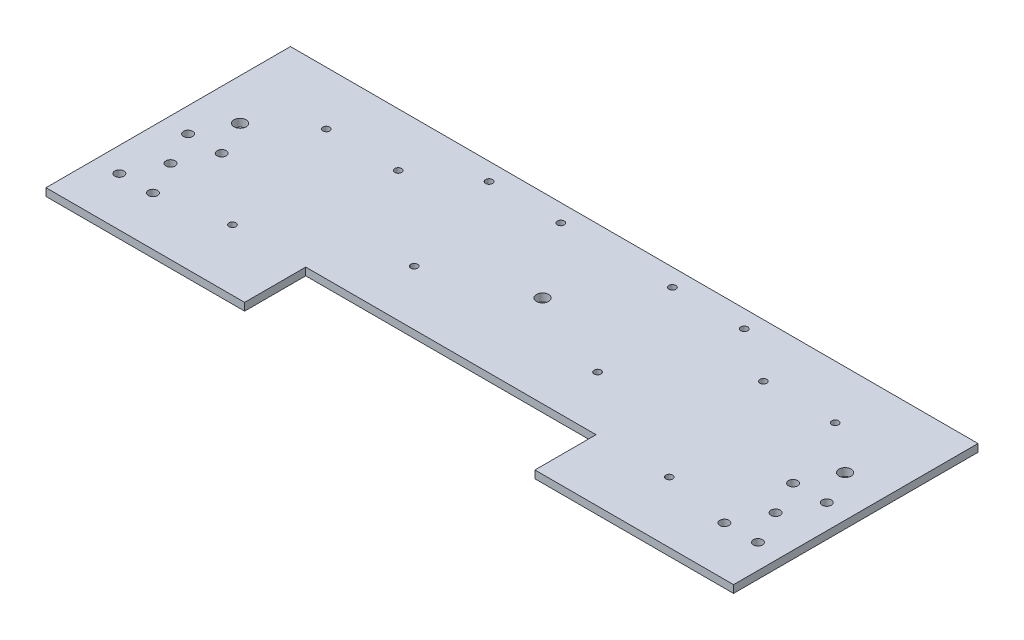
SolidWorks part; units mm, degrees
ref_plane "前视基准面" through (0, 0, 0) normal (0, 0, 1) x (1, 0, 0)
ref_plane "上视基准面" through (0, 0, 0) normal (0, 1, 0) x (1, 0, 0)
ref_plane "右视基准面" through (0, 0, 0) normal (1, 0, 0) x (0, 0, -1)
sketch "草图1" plane through (0, 0, 0) normal (0, 1, 0) x (1, 0, 0)
  line L1 (0, 0) -> (450, 0)
  line L2 (0, 0) -> (0, 120)
  line L3 (0, 120) -> (450, 120)
  line L4 (450, 0) -> (450, 120)
  dimension "D1" = 450
  dimension "D2" = 120
extrude "凸台-拉伸1" add sketch "草图1" along normal blind 5
sketch "草图2" plane through (0, 5, 0) normal (0, 1, 0) x (1, 0, 0)
  line L0 (0, 60) -> (450, 60) construction
  line L1 (0, 120) -> (0, 0) construction
  line L2 (450, 0) -> (450, 120) construction
  line L3 (225, 120) -> (225, 0) construction
  line L4 (450, 120) -> (0, 120) construction
  line L5 (0, 0) -> (450, 0) construction
  circle A0 centre (225, 60) radius 4
  circle A1 centre (27, 60) radius 4
  circle A2 centre (423, 60) radius 4
  dimension "D2" = 8
  dimension "D3" = 8
  dimension "D4" = 396
  dimension "D1" = 60
extrude "切除-拉伸1" cut sketch "草图2" against normal through all
sketch "草图3" plane through (0, 5, 0) normal (0, 1, 0) x (1, 0, 0)
  line L0 (0, 36) -> (450, 36) construction
  line L1 (0, 120) -> (0, 0) construction
  line L2 (450, 0) -> (450, 120) construction
  line L3 (0, 108.5) -> (450, 108.5) construction
  line L4 (225, 0) -> (225, 120) construction
  line L5 (0, 0) -> (450, 0) construction
  line L6 (450, 120) -> (0, 120) construction
  line L7 (165, 0) -> (165, 120) construction
  line L8 (285, 0) -> (285, 120) construction
  circle A0 centre (165, 36) radius 2.25
  circle A1 centre (141.5, 108.5) radius 2.25
  circle A2 centre (188.5, 108.5) radius 2.25
  circle A3 centre (285, 36) radius 2.25
  circle A4 centre (261.5, 108.5) radius 2.25
  circle A5 centre (308.5, 108.5) radius 2.25
  dimension "D4" = 47
  dimension "D5" = 4.5
  dimension "D6" = 4.5
  dimension "D1" = 36
  dimension "D2" = 72.5
  dimension "D3" = 60
extrude "切除-拉伸2" cut sketch "草图3" against normal through all
sketch "草图4" plane through (0, 5, 0) normal (0, 1, 0) x (1, 0, 0)
  line L0 (225, 0) -> (225, 120) construction
  line L1 (0, 0) -> (130, 0)
  line L2 (0, 0) -> (0, -40)
  line L3 (0, -40) -> (130, -40)
  line L4 (130, 0) -> (130, -40)
  line L5 (0, 0) -> (450, 0) construction
  line L6 (450, 120) -> (0, 120) construction
  line L7 (450, 0) -> (450, -40)
  line L8 (450, -40) -> (320, -40)
  line L9 (320, 0) -> (320, -40)
  line L10 (450, 0) -> (320, 0)
  dimension "D1" = 130
  dimension "D2" = 40
extrude "凸台-拉伸2" add sketch "草图4" against normal blind 5
sketch "草图5" plane through (0, 5, 0) normal (0, 1, 0) x (1, 0, 0)
  line L0 (225, 120) -> (225, 0) construction
  line L1 (450, 120) -> (0, 120) construction
  line L2 (130, 0) -> (320, 0) construction
  line L3 (82, 120) -> (82, -40) construction
  line L4 (0, -40) -> (130, -40) construction
  circle A0 centre (82, 0) radius 2.25
  circle A1 centre (58.5, 85) radius 2.25
  circle A2 centre (105.5, 85) radius 2.25
  circle A3 centre (368, 0) radius 2.25
  circle A4 centre (344.5, 85) radius 2.25
  circle A5 centre (391.5, 85) radius 2.25
  dimension "D1" = 4.5
  dimension "D2" = 4.5
  dimension "D4" = 47
  dimension "D5" = 85
  dimension "D6" = 0
  dimension "D3" = 143
extrude "切除-拉伸3" cut sketch "草图5" against normal through all
sketch "草图6" plane through (0, 5, 0) normal (0, 1, 0) x (1, 0, 0)
  line L0 (390, 60) -> (390, -40) construction
  line L1 (450, -40) -> (330, -40) construction
  line L2 (450, -40) -> (450, 60) construction
  line L3 (450, 60) -> (330, 60) construction
  line L4 (330, -40) -> (330, 60) construction
  line L5 (330, 10) -> (450, 10) construction
  line L6 (225, 0) -> (225, 120) construction
  line L7 (130, 0) -> (320, 0) construction
  line L8 (450, 120) -> (0, 120) construction
  circle A0 centre (415, 45) radius 3
  circle A1 centre (365, 45) radius 3
  circle A2 centre (365, -25) radius 3
  circle A3 centre (415, -25) radius 3
  circle A4 centre (85, -25) radius 3
  circle A5 centre (35, -25) radius 3
  circle A6 centre (35, 45) radius 3
  circle A7 centre (85, 45) radius 3
  dimension "D3" = 6
  dimension "D4" = 70
  dimension "D5" = 50
  dimension "D1" = 120
  dimension "D2" = 100
sketch "草图7" plane through (0, 5, 0) normal (0, 1, 0) x (1, 0, 0)
  line L0 (16, -8) -> (16, 37) construction
  line L1 (16, -8) -> (38, -8) construction
  line L2 (16, 37) -> (38, 37) construction
  line L3 (38, -8) -> (38, 37) construction
  line L4 (16, -8) -> (38, 37) construction
  line L5 (16, 37) -> (38, -8) construction
  line L6 (27, 37) -> (27, -8) construction
  line L7 (38, 14.5) -> (16, 14.5) construction
  line L8 (0, 120) -> (0, -40) construction
  line L9 (225, 0) -> (225, 120) construction
  circle A0 centre (38, 37) radius 3
  circle A1 centre (16, 37) radius 3
  circle A2 centre (16, -8) radius 3
  circle A3 centre (38, -8) radius 3
  circle A4 centre (27, 14.5) radius 3
  circle A5 centre (412, 37) radius 3
  circle A6 centre (434, 37) radius 3
  circle A7 centre (434, -8) radius 3
  circle A8 centre (423, 14.5) radius 3
  circle A9 centre (412, -8) radius 3
  point P1 (27, 14.5)
  dimension "D1" = 6
  dimension "D2" = 6
  dimension "D4" = 27
  dimension "D5" = 22
  dimension "D6" = 45
  dimension "D3" = 14.5
extrude "切除-拉伸4" cut sketch "草图7" against normal through all
